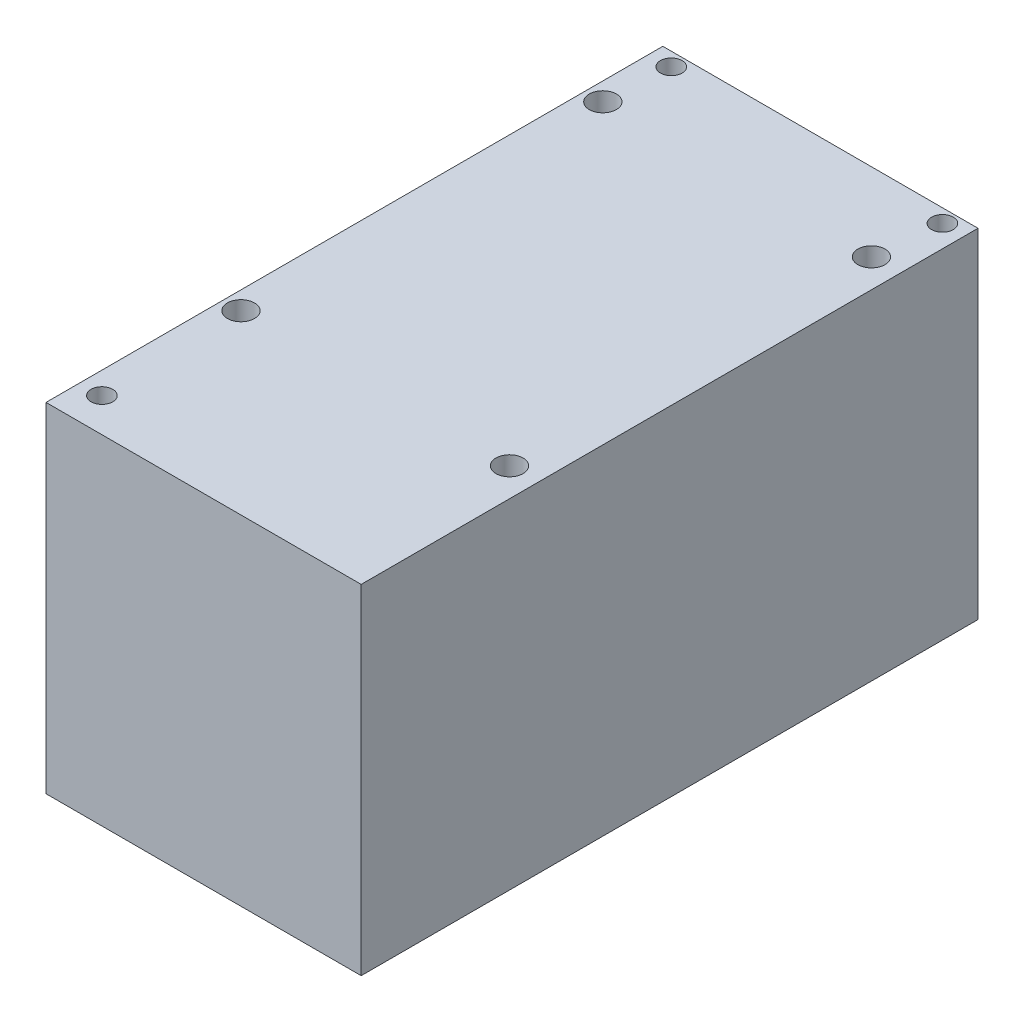
SolidWorks part; units mm, degrees
ref_plane "前视基准面" through (0, 0, 0) normal (0, 0, 1) x (1, 0, 0)
ref_plane "上视基准面" through (0, 0, 0) normal (0, 1, 0) x (1, 0, 0)
ref_plane "右视基准面" through (0, 0, 0) normal (1, 0, 0) x (0, 0, -1)
other "Configuration Table"
sketch "草图1" plane through (0, 0, 0) normal (0, 1, 0) x (1, 0, 0)
  line L0 (-20, 43.5) -> (-20, -45.5) construction
  line L1 (-23.25, -45.5) -> (23.25, -45.5)
  line L2 (-23.25, -45.5) -> (-23.25, 45.5)
  line L3 (-23.25, 45.5) -> (23.25, 45.5)
  line L4 (23.25, -45.5) -> (23.25, 45.5)
  line L5 (0, 45.5) -> (0, -45.5) construction
  line L6 (-23.25, 0) -> (23.25, 0) construction
  circle A0 centre (20, 43.5) radius 1.6
  circle A1 centre (-20, 43.5) radius 1.6
  circle A2 centre (-20, -40.5) radius 1.6
  point P0 (0, 0)
  dimension "D5" = 3.2
  dimension "D6" = 3.2
  dimension "D1" = 46.5
  dimension "D2" = 91
  dimension "D3" = 2
  dimension "D4" = 20
  dimension "D7" = 5
extrude "凸台-拉伸1" add sketch "草图1" along normal blind 50
sketch "草图2" plane through (0, 50, 0) normal (0, 1, 0) x (1, 0, 0)
  line L1 (-23.25, 45.5) -> (23.25, 45.5)
  line L2 (-23.25, 45.5) -> (-23.25, -45.5)
  line L3 (-23.25, -45.5) -> (23.25, -45.5)
  line L4 (23.25, 45.5) -> (23.25, -45.5)
  point P6 (19.042, -19.406)
  dimension "D1" = 4.208
  dimension "D2" = 26.094
sketch "草图3" plane through (0, 50, 0) normal (0, 1, 0) x (1, 0, 0)
  point P0 (19.042, -19.406)
hole_wizard "孔1" positions "草图3" profile "草图4" legacy end condition through all
sketch "草图4" plane through (19.042, 50, 19.406) normal (1, 0, 0) x (0, 0, 1)
  line L0 (0, 0) -> (0, 50)
  line L1 (0, 50) -> (2, 50)
  line L2 (2, 50) -> (2, 0)
  line L3 (2, 0) -> (0, 0)
  line L4 (0, 110) -> (0, -10) construction
  dimension "直径" = 4
  dimension "深度" = 50
sketch "草图5" plane through (0, 50, 0) normal (0, 1, 0) x (1, 0, 0)
  line L1 (19.042, -19.406) -> (-20.583, -19.406)
  line L2 (19.042, -19.406) -> (19.042, 33.984)
  line L3 (19.042, 33.984) -> (-20.583, 33.984)
  line L4 (-20.583, -19.406) -> (-20.583, 33.984)
  dimension "D1" = 53.39
  dimension "D2" = 39.625
sketch "草图6" plane through (0, 50, 0) normal (0, 1, 0) x (1, 0, 0)
  point P0 (19.042, 33.984)
  point P3 (-20.583, 33.984)
  point P6 (-20.583, -19.406)
hole_wizard "孔2" positions "草图6" profile "草图7" legacy
sketch "草图7" plane through (19.042, 50, -33.984) normal (1, 0, 0) x (0, 0, 1)
  line L0 (0, 0) -> (0, 100)
  line L1 (0, 100) -> (2, 100)
  line L2 (2, 100) -> (2, 0)
  line L3 (2, 0) -> (0, 0)
  line L4 (0, 110) -> (0, -10) construction
  dimension "直径" = 4
  dimension "深度" = 100
